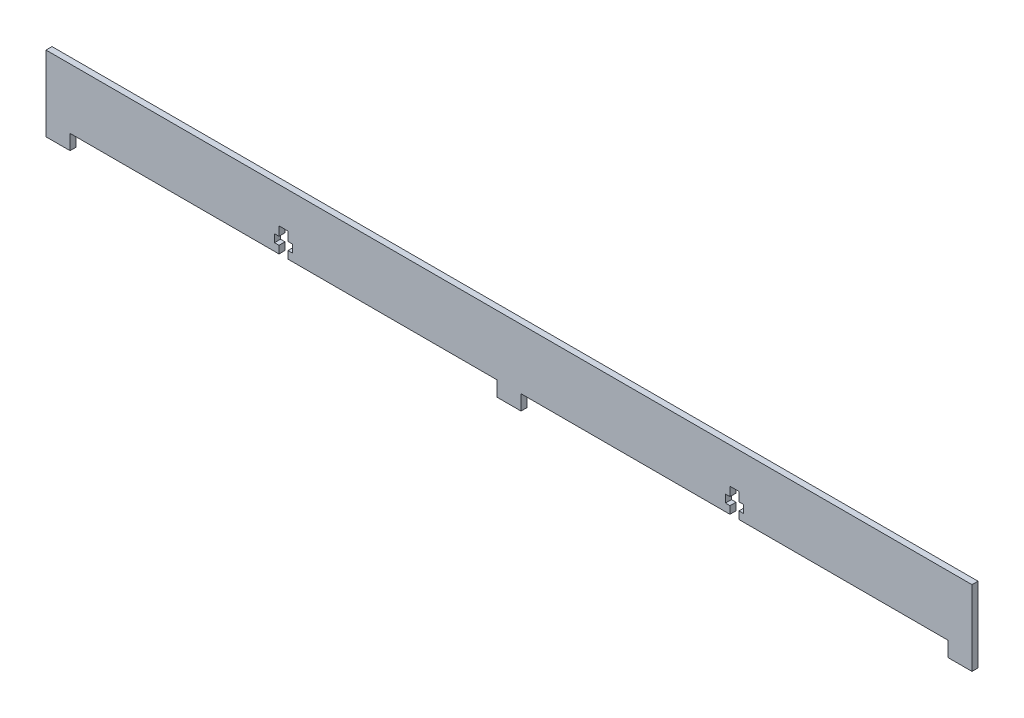
SolidWorks part; units mm, degrees
ref_plane "前视基准面" through (0, 0, 0) normal (0, 0, 1) x (1, 0, 0)
ref_plane "上视基准面" through (0, 0, 0) normal (0, 1, 0) x (1, 0, 0)
ref_plane "右视基准面" through (0, 0, 0) normal (1, 0, 0) x (0, 0, -1)
sketch "草图1" plane through (0, 0, 0) normal (0, 0, 1) x (1, 0, 0)
  line L0 (-229, -5) -> (-229, 20) construction
  line L13 (-229, 20) -> (71, 20)
  line L14 (-71, 0) -> (-71, -5)
  line L17 (-79, -5) -> (-71, -5) construction
  line L19 (79, -5) -> (71, -5)
  line L20 (-151.5, 8.1) -> (-148.5, 8.1)
  line L21 (-75, -5) -> (-75, 3.8) construction
  line L22 (-71, -5) -> (-79, -5)
  line L23 (-1.5, 0) -> (-71, 0)
  line L24 (3, 2.5) -> (3, 5.1)
  line L25 (71, 0) -> (71, -5)
  line L26 (3, 5.1) -> (1.5, 5.1)
  line L27 (1.5, 5.1) -> (1.5, 8.1)
  line L29 (-1.5, 5.1) -> (-1.5, 8.1)
  line L30 (-3, 5.1) -> (-1.5, 5.1)
  line L31 (-3, 2.5) -> (-3, 5.1)
  line L33 (1.5, 2.5) -> (3, 2.5)
  line L34 (-1.5, 2.5) -> (-3, 2.5)
  line L36 (-148.5, 0) -> (-79, 0)
  line L37 (-79, 0) -> (-79, -5)
  line L38 (1.5, 8.1) -> (-1.5, 8.1)
  line L40 (-1.5, 2.5) -> (-1.5, 0)
  line L41 (1.5, 2.5) -> (1.5, 0)
  line L43 (79, -5) -> (79, 0)
  line L44 (79, 0) -> (79, 20)
  line L45 (79, 20) -> (71, 20)
  line L46 (-229, 0) -> (-229, 20)
  line L47 (-229, -5) -> (-229, 0)
  line L49 (-148.5, 2.5) -> (-147, 2.5)
  line L50 (-151.5, 2.5) -> (-153, 2.5)
  line L51 (-151.5, 0) -> (-151.5, 2.5)
  line L52 (-147, 2.5) -> (-147, 5.1)
  line L53 (-147, 5.1) -> (-148.5, 5.1)
  line L54 (-148.5, 5.1) -> (-148.5, 8.1)
  line L56 (-151.5, 5.1) -> (-151.5, 8.1)
  line L57 (-153, 5.1) -> (-151.5, 5.1)
  line L58 (-153, 2.5) -> (-153, 5.1)
  line L59 (-148.5, 2.5) -> (-148.5, 0)
  line L64 (-221, -5) -> (-229, -5) construction
  line L68 (-221, 0) -> (-221, -5)
  line L69 (-151.5, 0) -> (-221, 0)
  line L71 (-229, -5) -> (-221, -5)
  line L73 (1.5, 0) -> (71, 0)
  line L83 (71, 0) -> (71, -5)
extrude "凸台-拉伸1" add sketch "草图1" along normal blind 2
sketch "草图2" plane through (0, 0, 0) normal (0, -1, 0) x (1, 0, 0)
  line L0 (1.5, 0) -> (-1.5, 2)
  circle A0 centre (0, 1) radius 1.5
